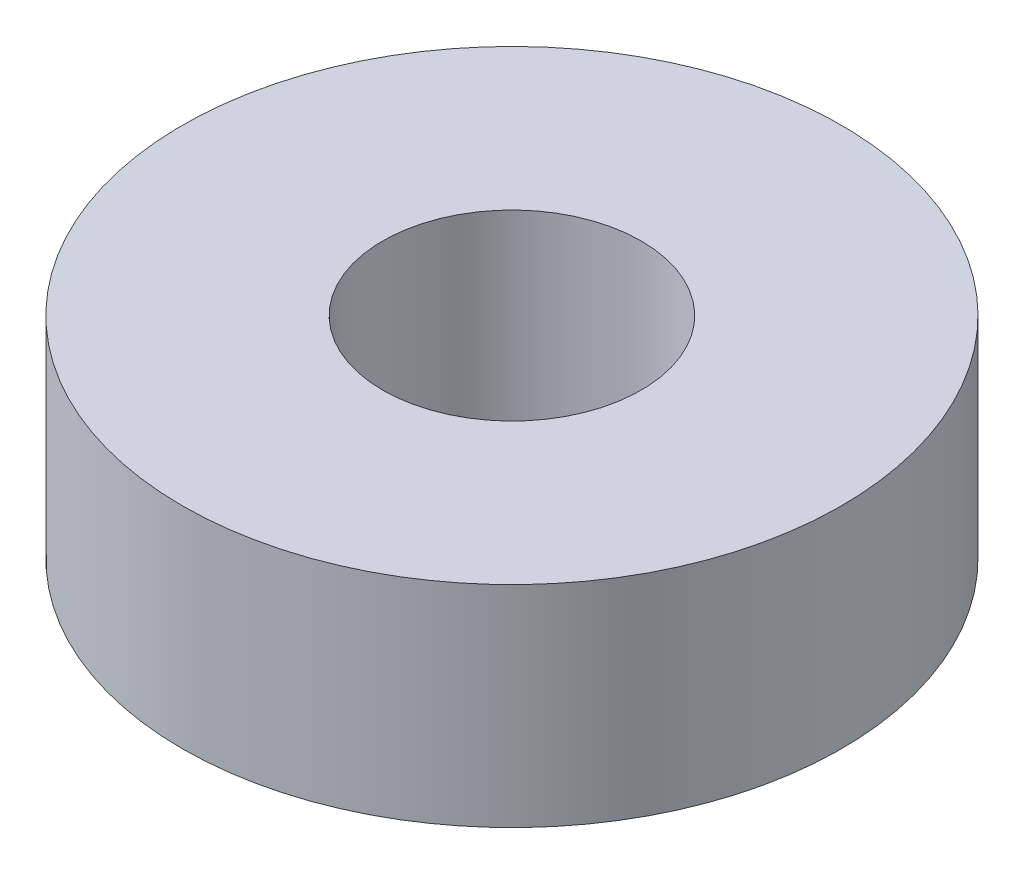
SolidWorks part; units mm, degrees
ref_plane "Front Plane" through (0, 0, 0) normal (0, 0, 1) x (1, 0, 0)
ref_plane "Top Plane" through (0, 0, 0) normal (0, 1, 0) x (1, 0, 0)
ref_plane "Right Plane" through (0, 0, 0) normal (1, 0, 0) x (0, 0, -1)
sketch "Sketch1" plane through (0, 0, 0) normal (0, 1, 0) x (1, 0, 0)
  circle A0 centre (0, 0) radius 10.9625
  circle A1 centre (0, 0) radius 4.3
  dimension "D1" = 21.925
  dimension "D2" = 8.6
extrude "Boss-Extrude1" add sketch "Sketch1" along normal blind 7
